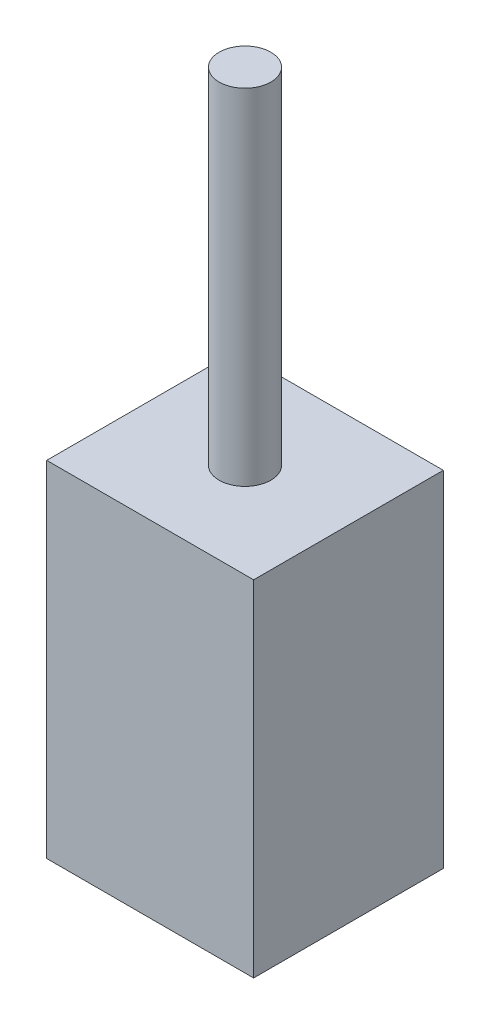
SolidWorks part; units mm, degrees
ref_plane "Front Plane" through (0, 0, 0) normal (0, 0, 1) x (1, 0, 0)
ref_plane "Top Plane" through (0, 0, 0) normal (0, 1, 0) x (1, 0, 0)
ref_plane "Right Plane" through (0, 0, 0) normal (1, 0, 0) x (0, 0, -1)
sketch "Sketch1" plane through (0, 0, 0) normal (0, 1, 0) x (1, 0, 0)
  line L1 (0, 0) -> (12, 0)
  line L2 (0, 0) -> (0, 11)
  line L3 (0, 11) -> (12, 11)
  line L4 (12, 0) -> (12, 11)
  dimension "D1" = 12
  dimension "D2" = 11
extrude "Boss-Extrude1" add sketch "Sketch1" along normal blind 20
sketch "Sketch2" plane through (0, 20, 0) normal (0, 1, 0) x (1, 0, 0)
  line L0 (-0.6033, 5.5) -> (12.6033, 5.5) construction
  line L1 (6, -0.6264) -> (6, 11.6264) construction
  line L2 (12, 11) -> (0, 11) construction
  line L3 (0, 11) -> (0, 0) construction
  circle A0 centre (6, 5.5) radius 1.5
  point P6 (6, 11)
  point P9 (0, 5.5)
  point P12 (6.71, 5.5)
  dimension "D1" = 3
extrude "Boss-Extrude2" add sketch "Sketch2" along normal blind 20
